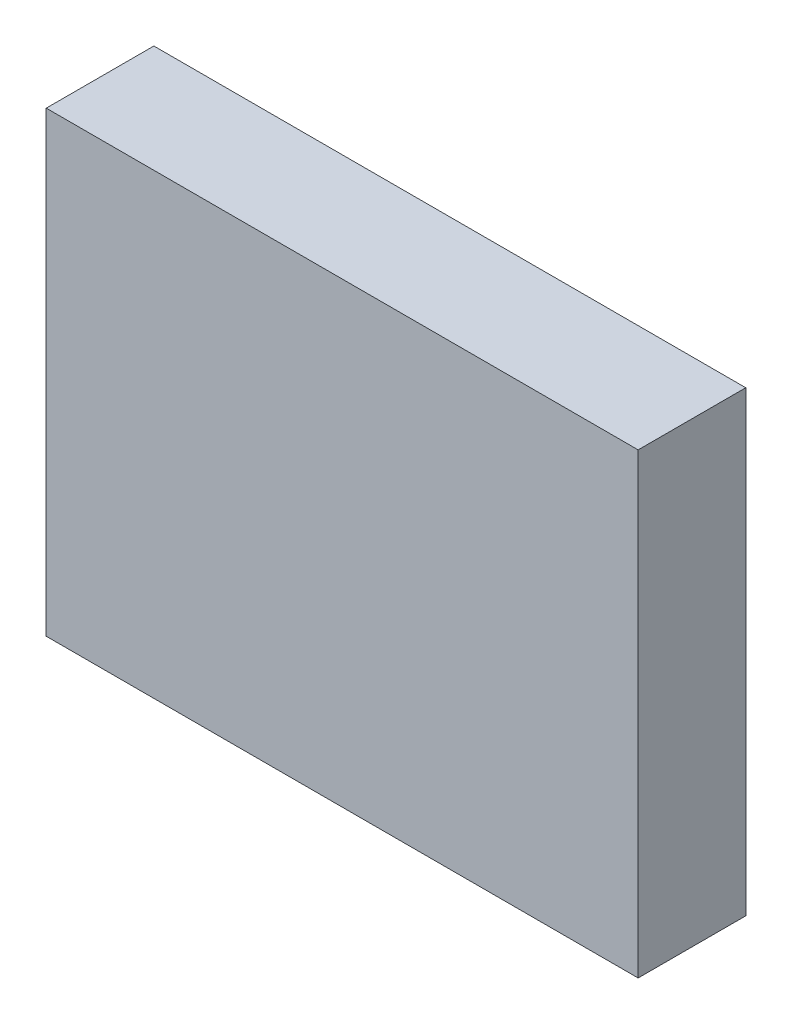
SolidWorks part; units mm, degrees
material "converter"
ref_plane "Front Plane" through (0, 0, 0) normal (0, 0, 1) x (1, 0, 0)
ref_plane "Top Plane" through (0, 0, 0) normal (0, 1, 0) x (1, 0, 0)
ref_plane "Right Plane" through (0, 0, 0) normal (1, 0, 0) x (0, 0, -1)
sketch "Sketch1" plane through (0, 0, 0) normal (0, 0, 1) x (1, 0, 0)
  line L1 (0, 0) -> (22, 0)
  line L2 (0, 0) -> (0, 17)
  line L3 (0, 17) -> (22, 17)
  line L4 (22, 0) -> (22, 17)
  dimension "D1" = 22
  dimension "D2" = 17
extrude "Boss-Extrude1" add sketch "Sketch1" along normal blind 4
